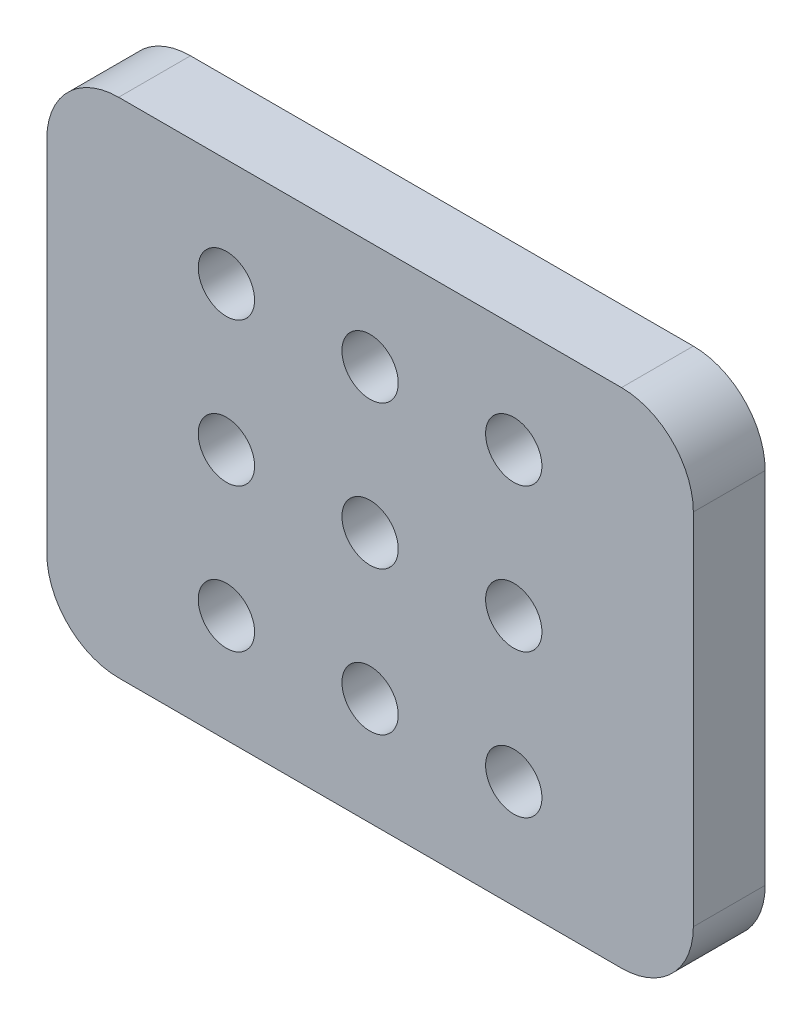
SolidWorks part; units mm, degrees
material "6061-T6 (SS)"
ref_plane "Front Plane" through (0, 0, 0) normal (0, 0, 1) x (1, 0, 0)
ref_plane "Top Plane" through (0, 0, 0) normal (0, 1, 0) x (1, 0, 0)
ref_plane "Right Plane" through (0, 0, 0) normal (1, 0, 0) x (0, 0, -1)
sketch "Sketch1" plane through (0, 0, 0) normal (0, 0, 1) x (1, 0, 0)
  line L0 (31.75, 50.8) -> (31.75, 0) construction
  line L1 (0, 0) -> (63.5, 0)
  line L2 (0, 0) -> (0, 50.8)
  line L3 (0, 50.8) -> (63.5, 50.8)
  line L4 (63.5, 0) -> (63.5, 50.8)
  line L5 (3.175, 47.625) -> (60.325, 47.625)
  line L6 (60.325, 3.175) -> (60.325, 47.625)
  line L7 (3.175, 3.175) -> (60.325, 3.175)
  line L8 (3.175, 3.175) -> (3.175, 47.625)
  circle A0 centre (31.75, 25.4) radius 2.4892
  circle A1 centre (31.75, 38.1) radius 2.4892
  circle A2 centre (31.75, 12.7) radius 2.4892
  circle A3 centre (44.45, 12.7) radius 2.4892
  circle A4 centre (44.45, 25.4) radius 2.4892
  circle A5 centre (44.45, 38.1) radius 2.4892
  circle A6 centre (19.05, 38.1) radius 2.4892
  circle A7 centre (19.05, 25.4) radius 2.4892
  circle A8 centre (19.05, 12.7) radius 2.4892
  dimension "D3" = 4.9784
  dimension "D4" = 12.7
  dimension "D1" = 63.5
  dimension "D2" = 50.8
  dimension "D5" = 12.7
  dimension "D8" = 12.7
  dimension "D9" = 12.7
  dimension "D10" = 3.175
  dimension "D6" = 2
  dimension "D7" = 2
extrude "Boss-Extrude1" add sketch "Sketch1" along normal mid plane 6.35 contours L5 L0 A1 A0 A2 L7 L6 A3 A4 A5 | L0 L5 L8 L7 A2 A0 A1 A8 A7 A6
fillet "Fillet1" radius 6.35 4 edges at (60.325, 3.175, 0) (3.175, 3.175, 0) (3.175, 47.625, 0) (60.325, 47.625, 0)
